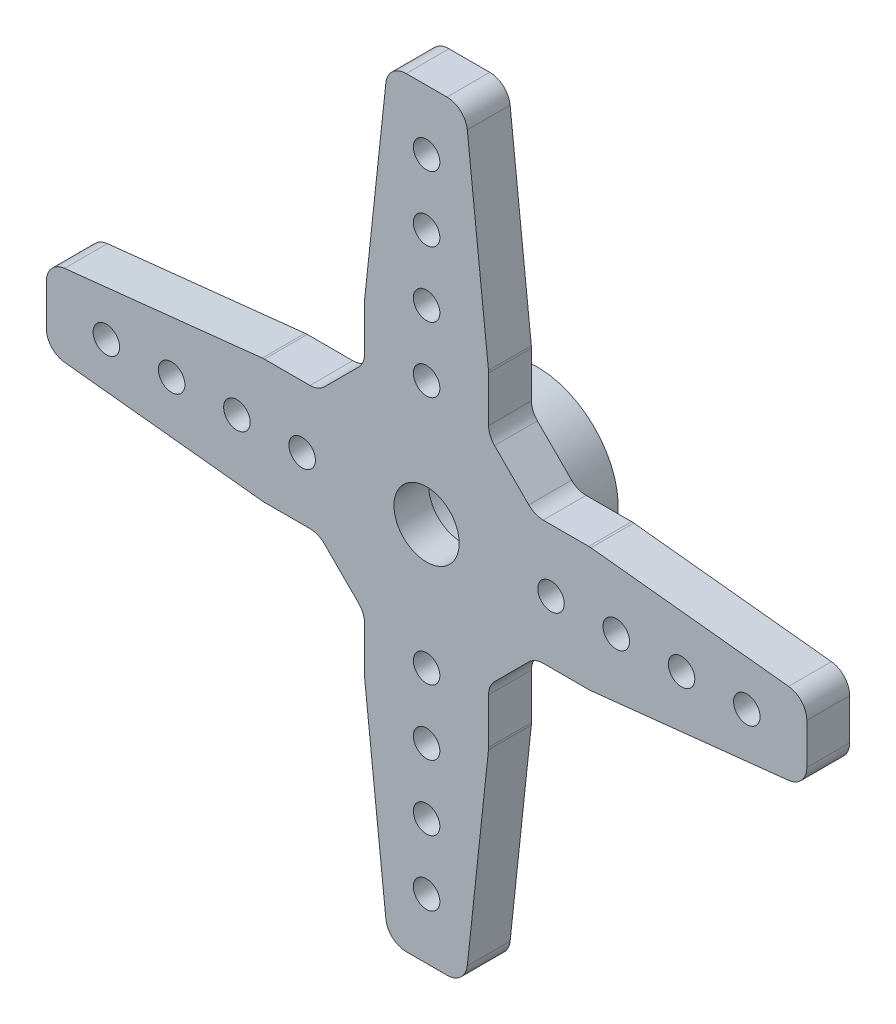
SolidWorks part; units mm, degrees
ref_plane "Front Plane" through (0, 0, 0) normal (0, 0, 1) x (1, 0, 0)
ref_plane "Top Plane" through (0, 0, 0) normal (0, 1, 0) x (1, 0, 0)
ref_plane "Right Plane" through (0, 0, 0) normal (1, 0, 0) x (0, 0, -1)
sketch "Sketch1" plane through (0, 0, 0) normal (0, 0, 1) x (1, 0, 0)
  circle A0 centre (0, 0) radius 4
  circle A1 centre (0, 0) radius 1.6
  dimension "D1" = 8
extrude "Boss-Extrude1" add sketch "Sketch1" along normal blind 5.4
sketch "Sketch2" plane through (0, 0, 5.4) normal (0, 0, 1) x (1, 0, 0)
  line L0 (0, 0) -> (0, 3.3206) construction
  line L1 (0, 0) -> (2.0806, 0) construction
  line L2 (0, 0) -> (1.5661, 1.5661) construction
  line L3 (4.1719, 4.1719) -> (3.3335, 5.0104)
  line L4 (3.0406, 5.7175) -> (3.0406, 7.9499)
  line L5 (3.0349, 8.0564) -> (1.9958, 17.7489)
  line L6 (1.0015, 18.6423) -> (-1.0015, 18.6423)
  line L7 (-3.0349, 8.0564) -> (-1.9958, 17.7489)
  line L8 (-3.0406, 5.7175) -> (-3.0406, 7.9499)
  line L9 (-4.1719, 4.1719) -> (-3.3335, 5.0104)
  line L10 (8.0564, 3.0349) -> (17.7489, 1.9958)
  line L11 (18.6423, -1.0015) -> (18.6423, 1.0015)
  line L12 (8.0564, -3.0349) -> (17.7489, -1.9958)
  line L13 (5.7175, -3.0406) -> (7.9499, -3.0406)
  line L14 (4.1719, -4.1719) -> (5.0104, -3.3335)
  line L15 (5.7175, 3.0406) -> (7.9499, 3.0406)
  line L16 (4.1719, 4.1719) -> (5.0104, 3.3335)
  line L17 (3.0349, -8.0564) -> (1.9958, -17.7489)
  line L18 (-1.0015, -18.6423) -> (1.0015, -18.6423)
  line L19 (-3.0349, -8.0564) -> (-1.9958, -17.7489)
  line L20 (-3.0406, -5.7175) -> (-3.0406, -7.9499)
  line L21 (-4.1719, -4.1719) -> (-3.3335, -5.0104)
  line L22 (3.0406, -5.7175) -> (3.0406, -7.9499)
  line L23 (4.1719, -4.1719) -> (3.3335, -5.0104)
  line L24 (-8.0564, -3.0349) -> (-17.7489, -1.9958)
  line L25 (-18.6423, 1.0015) -> (-18.6423, -1.0015)
  line L26 (-8.0564, 3.0349) -> (-17.7489, 1.9958)
  line L27 (-5.7175, 3.0406) -> (-7.9499, 3.0406)
  line L28 (-4.1719, 4.1719) -> (-5.0104, 3.3335)
  line L29 (-5.7175, -3.0406) -> (-7.9499, -3.0406)
  line L30 (-4.1719, -4.1719) -> (-5.0104, -3.3335)
  arc A1 (-3.0406, 5.7175) -> (-3.3335, 5.0104) centre (-4.0406, 5.7175) cw
  arc A2 (-1.9958, 17.7489) -> (-1.0015, 18.6423) centre (-1.0015, 17.6423) cw
  arc A3 (1.9958, 17.7489) -> (1.0015, 18.6423) centre (1.0015, 17.6423) ccw
  arc A4 (3.3335, 5.0104) -> (3.0406, 5.7175) centre (4.0406, 5.7175) cw
  arc A5 (-3.0349, 8.0564) -> (-3.0406, 7.9499) centre (-2.0406, 7.9499) ccw
  arc A6 (3.0406, 7.9499) -> (3.0349, 8.0564) centre (2.0406, 7.9499) ccw
  arc A7 (17.7489, 1.9958) -> (18.6423, 1.0015) centre (17.6423, 1.0015) cw
  arc A8 (17.7489, -1.9958) -> (18.6423, -1.0015) centre (17.6423, -1.0015) ccw
  arc A9 (5.0104, -3.3335) -> (5.7175, -3.0406) centre (5.7175, -4.0406) cw
  arc A10 (8.0564, 3.0349) -> (7.9499, 3.0406) centre (7.9499, 2.0406) ccw
  arc A11 (7.9499, -3.0406) -> (8.0564, -3.0349) centre (7.9499, -2.0406) ccw
  arc A12 (5.7175, 3.0406) -> (5.0104, 3.3335) centre (5.7175, 4.0406) cw
  arc A13 (1.9958, -17.7489) -> (1.0015, -18.6423) centre (1.0015, -17.6423) cw
  arc A14 (-1.9958, -17.7489) -> (-1.0015, -18.6423) centre (-1.0015, -17.6423) ccw
  arc A15 (-3.3335, -5.0104) -> (-3.0406, -5.7175) centre (-4.0406, -5.7175) cw
  arc A16 (3.0349, -8.0564) -> (3.0406, -7.9499) centre (2.0406, -7.9499) ccw
  arc A17 (-3.0406, -7.9499) -> (-3.0349, -8.0564) centre (-2.0406, -7.9499) ccw
  arc A18 (3.0406, -5.7175) -> (3.3335, -5.0104) centre (4.0406, -5.7175) cw
  arc A19 (-17.7489, -1.9958) -> (-18.6423, -1.0015) centre (-17.6423, -1.0015) cw
  arc A20 (-17.7489, 1.9958) -> (-18.6423, 1.0015) centre (-17.6423, 1.0015) ccw
  arc A21 (-5.0104, 3.3335) -> (-5.7175, 3.0406) centre (-5.7175, 4.0406) cw
  arc A22 (-8.0564, -3.0349) -> (-7.9499, -3.0406) centre (-7.9499, -2.0406) ccw
  arc A23 (-7.9499, 3.0406) -> (-8.0564, 3.0349) centre (-7.9499, 2.0406) ccw
  arc A24 (-5.7175, -3.0406) -> (-5.0104, -3.3335) centre (-5.7175, -4.0406) cw
  circle A25 centre (0, 0) radius 1.6
  circle A26 centre (0, 6.1) radius 0.65
  circle A27 centre (0, 9.3) radius 0.65
  circle A28 centre (0, 12.5) radius 0.65
  circle A29 centre (0, 15.7) radius 0.65
  circle A30 centre (15.7, 0) radius 0.65
  circle A31 centre (12.5, 0) radius 0.65
  circle A32 centre (9.3, 0) radius 0.65
  circle A33 centre (6.1, 0) radius 0.65
  circle A34 centre (0, -15.7) radius 0.65
  circle A35 centre (0, -12.5) radius 0.65
  circle A36 centre (0, -9.3) radius 0.65
  circle A37 centre (0, -6.1) radius 0.65
  circle A38 centre (-15.7, 0) radius 0.65
  circle A39 centre (-12.5, 0) radius 0.65
  circle A40 centre (-9.3, 0) radius 0.65
  circle A41 centre (-6.1, 0) radius 0.65
  point P26 (0, 18.6423)
  point P31 (-3.0406, 5.3033)
  point P34 (-1.9, 18.6423)
  point P37 (1.9, 18.6423)
  point P40 (3.0406, 5.3033)
  point P43 (-3.0406, 8.0033)
  point P46 (3.0406, 8.0033)
  point P99 (0, 0)
  point P128 (0, 0)
  dimension "D7" = 1
  dimension "D8" = 6.1
  dimension "D10" = 1.3
  dimension "D1" = 45
  dimension "D2" = 10.7
  dimension "D3" = 1.9
  dimension "D4" = 2.7
  dimension "D5" = 1.6
  dimension "D6" = 4
  dimension "D9" = 4
extrude "Boss-Extrude2" add sketch "Sketch2" against normal blind 2.1
sketch "Sketch3" plane through (0, 0, 0) normal (0, 0, -1) x (-1, 0, 0)
  circle A0 centre (0, 0) radius 2.5
  dimension "D1" = 5
extrude "Cut-Extrude1" cut sketch "Sketch3" against normal blind 3.7
